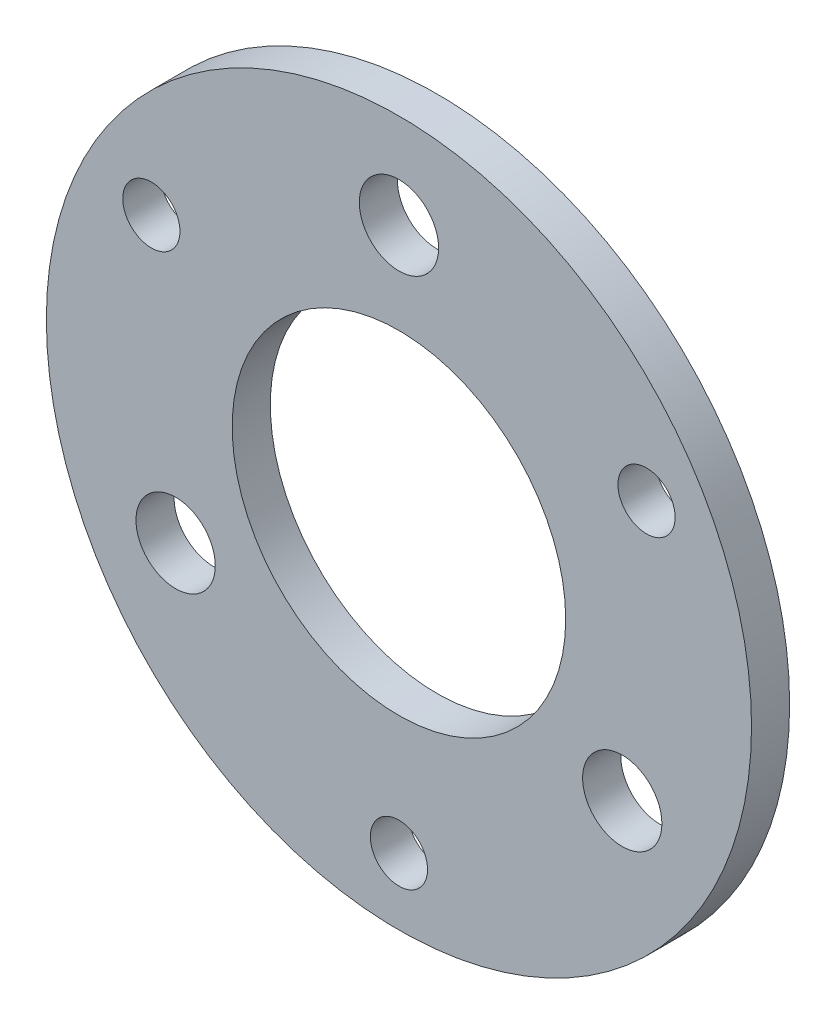
SolidWorks part; units mm, degrees
ref_plane "前视基准面" through (0, 0, 0) normal (0, 0, 1) x (1, 0, 0)
ref_plane "上视基准面" through (0, 0, 0) normal (0, 1, 0) x (1, 0, 0)
ref_plane "右视基准面" through (0, 0, 0) normal (1, 0, 0) x (0, 0, -1)
sketch "草图1" plane through (0, 0, 0) normal (0, 0, 1) x (1, 0, 0)
  line L0 (1.0322, 0.316) -> (1.0322, 8.6169) construction
  circle A0 centre (1.0322, 0.316) radius 15 construction
  circle A1 centre (1.0322, 0.316) radius 13.53 construction
  circle A2 centre (1.0322, 13.846) radius 2.08
  circle A3 centre (12.7495, -6.449) radius 2.08
  circle A4 centre (-10.6851, -6.449) radius 2.08
  circle A5 centre (1.0322, 0.316) radius 8.75
  circle A6 centre (-11.9582, 7.816) radius 1.5
  circle A7 centre (14.0226, 7.816) radius 1.5
  circle A8 centre (1.0322, -14.684) radius 1.5
  circle A9 centre (1.0322, 0.316) radius 18.5
extrude "凸台-拉伸1" add sketch "草图1" along normal blind 2 contours A9
